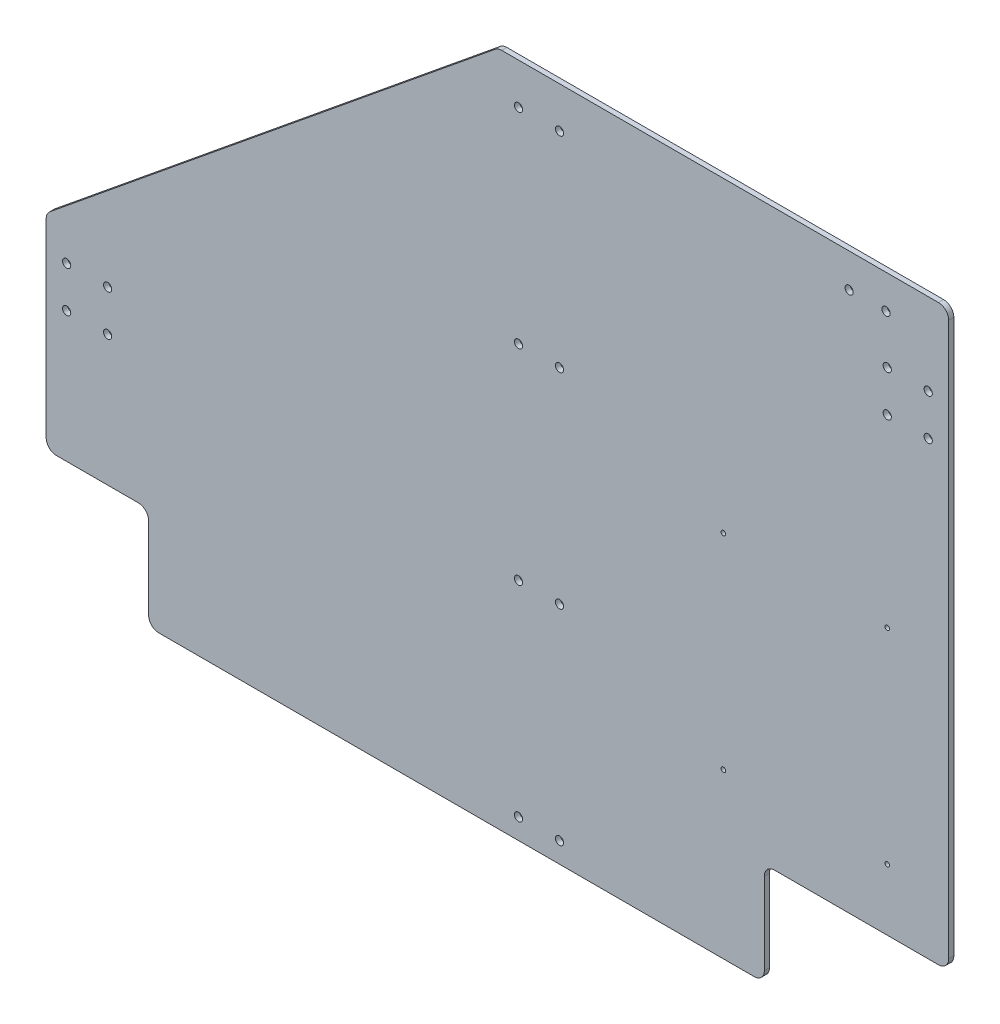
SolidWorks part; units mm, degrees
ref_plane "Front Plane" through (0, 0, 0) normal (0, 0, 1) x (1, 0, 0)
ref_plane "Top Plane" through (0, 0, 0) normal (0, 1, 0) x (1, 0, 0)
ref_plane "Right Plane" through (0, 0, 0) normal (1, 0, 0) x (0, 0, -1)
sketch "Sketch1" plane through (0, 0, 0) normal (0, 0, 1) x (1, 0, 0)
  line L1 (0, 0) -> (508.762, 0) construction
  line L2 (0, 0) -> (0, 419.1) construction
  line L3 (0, 419.1) -> (508.762, 419.1) construction
  line L4 (508.762, 0) -> (508.762, 419.1) construction
  line L5 (280.162, 0) -> (330.962, 0) construction
  line L6 (280.162, 0) -> (280.162, 419.1) construction
  line L7 (280.162, 419.1) -> (330.962, 419.1) construction
  line L8 (330.962, 0) -> (330.962, 419.1) construction
  line L9 (0, 0) -> (63.5, 0) construction
  line L10 (0, 0) -> (0, 63.5) construction
  line L11 (0, 63.5) -> (63.5, 63.5)
  line L12 (63.5, 0) -> (63.5, 63.5)
  line L13 (508.762, 0) -> (445.262, 0) construction
  line L14 (508.762, 0) -> (508.762, 63.5) construction
  line L15 (508.762, 63.5) -> (445.262, 63.5)
  line L16 (445.262, 0) -> (445.262, 63.5)
  line L17 (292.862, 12.7) -> (318.262, 12.7) construction
  line L18 (292.862, 12.7) -> (292.862, 139.7) construction
  line L19 (508.762, 63.5) -> (508.762, 419.1)
  line L20 (508.762, 419.1) -> (280.162, 419.1)
  line L21 (63.5, 0) -> (445.262, 0)
  line L22 (0, 63.5) -> (0, 190.5)
  line L23 (0, 190.5) -> (280.162, 419.1)
  line L24 (508.762, 419.1) -> (559.562, 419.1)
  line L25 (330.962, 381) -> (508.762, 381) construction
  line L26 (330.962, 381) -> (330.962, 330.2) construction
  line L27 (330.962, 330.2) -> (508.762, 330.2) construction
  line L28 (508.762, 381) -> (508.762, 330.2) construction
  line L29 (521.462, 368.3) -> (546.862, 368.3) construction
  line L30 (521.462, 368.3) -> (521.462, 342.9) construction
  line L31 (521.462, 342.9) -> (546.862, 342.9) construction
  line L32 (546.862, 368.3) -> (546.862, 342.9) construction
  line L33 (521.462, 368.3) -> (546.862, 342.9) construction
  line L34 (521.462, 342.9) -> (546.862, 368.3) construction
  line L35 (0, 0) -> (50.8, 0) construction
  line L36 (0, 0) -> (0, 182.5625) construction
  line L37 (0, 182.5625) -> (50.8, 182.5625) construction
  line L38 (50.8, 0) -> (50.8, 182.5625) construction
  line L39 (12.7, 169.8625) -> (38.1, 169.8625) construction
  line L40 (12.7, 169.8625) -> (12.7, 144.4625) construction
  line L41 (12.7, 144.4625) -> (38.1, 144.4625) construction
  line L42 (38.1, 169.8625) -> (38.1, 144.4625) construction
  line L43 (12.7, 169.8625) -> (38.1, 144.4625) construction
  line L44 (12.7, 144.4625) -> (38.1, 169.8625) construction
  line L45 (559.562, 419.1) -> (559.562, 63.5)
  line L46 (559.562, 63.5) -> (508.762, 63.5)
  circle A0 centre (318.262, 12.7) radius 2.54
  circle A1 centre (292.862, 12.7) radius 2.54
  circle A2 centre (292.862, 139.7) radius 2.54
  circle A3 centre (318.262, 139.7) radius 2.54
  circle A4 centre (292.862, 266.7) radius 2.54
  circle A5 centre (318.262, 266.7) radius 2.54
  circle A6 centre (292.862, 393.7) radius 2.54
  circle A7 centre (318.262, 393.7) radius 2.54
  circle A8 centre (521.462, 368.3) radius 2.54
  circle A9 centre (546.862, 368.3) radius 2.54
  circle A10 centre (546.862, 342.9) radius 2.54
  circle A11 centre (521.462, 342.9) radius 2.54
  circle A12 centre (12.7, 169.8625) radius 2.54
  circle A13 centre (38.1, 169.8625) radius 2.54
  circle A14 centre (38.1, 144.4625) radius 2.54
  circle A15 centre (12.7, 144.4625) radius 2.54
  point P41 (534.162, 355.6)
  point P53 (25.4, 157.1625)
  point P55 (25.4, 182.5625)
  dimension "D9" = 5.08
  dimension "D19" = 5.08
  dimension "D24" = 5.08
  dimension "20.03" = 508.762
  dimension "D2" = 419.1
  dimension "D3" = 50.8
  dimension "D4" = 177.8
  dimension "D5" = 63.5
  dimension "D6" = 63.5
  dimension "D7" = 25.4
  dimension "D8" = 12.7
  dimension "D10" = 12.7
  dimension "D12" = 127
  dimension "D13" = 127
  dimension "D14" = 50.8
  dimension "D15" = 38.1
  dimension "D16" = 12.7
  dimension "D17" = 12.7
  dimension "D18" = 25.4
  dimension "D20" = 182.5625
  dimension "D21" = 50.8
  dimension "D22" = 25.4
  dimension "D23" = 25.4
  dimension "D25" = 50.8
  dimension "D11" = 4
extrude "Boss-Extrude1" add sketch "Sketch1" along normal blind 3.175 contours L1 L16 L15 L4 L3 L2 L11 L12 | L46 L45 L24 L19
fillet "Fillet1" radius 6.35 9 edges at (280.162, 419.1, 1.5875) (445.262, 63.5, 1.5875) (445.262, 0, 1.5875) (63.5, 0, 1.5875) (63.5, 63.5, 1.5875) (0, 63.5, 1.5875) (0, 190.5, 1.5875) (559.562, 419.1, 1.5875) (559.562, 63.5, 1.5875)
sketch "Sketch2" [suppressed] plane through (0, 0, 3.175) normal (0, 0, 1) x (1, 0, 0)
  line L9 (167.64, 208.28) -> (167.64, 157.48) construction
  line L10 (116.84, 208.28) -> (116.84, 157.48) construction
  line L11 (66.04, 208.28) -> (66.04, 157.48) construction
  line L12 (0, 67.31) -> (0, 184.9667) construction
  line L13 (6.35, 60.96) -> (57.15, 60.96) construction
  circle A9 centre (66.04, 208.28) radius 2.54
  circle A10 centre (116.84, 208.28) radius 2.54
  circle A11 centre (167.64, 208.28) radius 2.54
  circle A12 centre (167.64, 157.48) radius 2.54
  circle A13 centre (116.84, 157.48) radius 2.54
  circle A14 centre (66.04, 157.48) radius 2.54
  dimension "D9" = 5.08
  dimension "D7" = 50.8
  dimension "D8" = 50.8
  dimension "D10" = 50.8
  dimension "D11" = 66.04
  dimension "D12" = 147.32
sketch "Sketch3" plane through (0, 0, 3.175) normal (0, 0, 1) x (1, 0, 0)
  line L1 (419.862, 228.6) -> (521.462, 228.6) construction
  line L2 (419.862, 228.6) -> (419.862, 101.6) construction
  line L3 (419.862, 101.6) -> (521.462, 101.6) construction
  line L4 (521.462, 228.6) -> (521.462, 101.6) construction
  line L5 (553.212, 63.5) -> (451.612, 63.5) construction
  line L7 (559.562, 412.75) -> (559.562, 69.85) construction
  circle A0 centre (521.462, 228.6) radius 1.4224
  circle A1 centre (419.862, 228.6) radius 1.4224
  circle A2 centre (419.862, 101.6) radius 1.4224
  circle A3 centre (521.462, 101.6) radius 1.4224
  dimension "D3" = 2.8448
  dimension "D1" = 101.6
  dimension "D2" = 127
  dimension "D4" = 38.1
  dimension "D5" = 38.1
extrude "Cut-Extrude3" cut sketch "Sketch3" against normal through all
sketch "Sketch4" [suppressed] plane through (0, 0, 3.175) normal (0, 0, 1) x (1, 0, 0)
  circle A0 centre (471.363, 392.8278) radius 19.113
extrude "Cut-Extrude4" [suppressed] cut sketch "Sketch4" against normal blind 1320.8
sketch "Sketch5" plane through (0, 0, 3.175) normal (0, 0, 1) x (1, 0, 0)
  line L1 (553.212, 419.1) -> (282.4239, 419.1) construction
  line L2 (559.562, 412.75) -> (559.562, 69.85) construction
  circle A0 centre (520.7, 398.145) radius 2.54
  circle A1 centre (497.84, 398.145) radius 2.54
  dimension "D2" = 5.08
  dimension "D1" = 38.862
  dimension "D3" = 22.86
  dimension "D4" = 20.955
extrude "Cut-Extrude5" cut sketch "Sketch5" against normal through all
sketch "Sketch6" [suppressed] plane through (0, 0, 0) normal (0, 0, -1) x (-1, 0, 0)
  circle A0 centre (-507.5341, 412.7222) radius 2.5
  circle A1 centre (-405.9341, 412.7222) radius 2.5
  circle A2 centre (-507.5341, 196.8222) radius 2.5
  circle A3 centre (-513.3621, 110.9575) radius 3.429
  circle A4 centre (-456.5246, 139.5278) radius 3.429
  arc A5 (-513.4, 114.3863) -> (-513.3242, 107.5287) centre (-513.3621, 110.9575) ccw construction
  arc A6 (-513.3242, 107.5287) -> (-513.4, 114.3863) centre (-513.3621, 110.9575) ccw construction
  circle A7 centre (-405.9341, 196.8222) radius 2.5
  circle A8 centre (-507.5341, 412.7222) radius 2.5 construction
  circle A9 centre (-417.195, 144.1893) radius 1.905
  circle A10 centre (-369.443, 144.1893) radius 1.905
  circle A11 centre (-417.1927, 101.1363) radius 1.905
  circle A12 centre (-369.443, 101.1363) radius 1.905
  circle A13 centre (-369.443, 101.1363) radius 1.905 construction
extrude "Cut-Extrude6" [suppressed] cut sketch "Sketch6" against normal blind 5.08
sketch "Sketch7" plane through (0, 0, 3.175) normal (0, 0, 1) x (1, 0, 0)
  line L0 (-877.5949, 431.8) -> (49122.4051, 431.8) construction
  line L1 (-12.7, -862.3857) -> (-12.7, 49137.6143) construction
  line L2 (-880.3611, -12.7) -> (49119.6389, -12.7) construction
  line L3 (553.212, 419.1) -> (282.4239, 419.1) construction
  line L4 (0, 69.85) -> (0, 187.4857) construction
  line L5 (69.85, 0) -> (438.912, 0) construction
  circle A0 centre (95.5613, 249.583) radius 8.2977
  circle A1 centre (204.2244, 338.5669) radius 12.1725
  circle A2 centre (84.4383, 22.6214) radius 10.7037
  circle A3 centre (424.1175, 22.6214) radius 6.6795
  point P5 (-12.7, 431.8)
  point P7 (-12.7, -12.7)
  point P14 (95.5613, 249.583)
  point P17 (204.2244, 338.5669)
  point P18 (84.4383, 22.6214)
  point P19 (424.1175, 22.6214)
  dimension "D1" = 12.7
  dimension "D2" = 12.7
  dimension "D3" = 12.7
